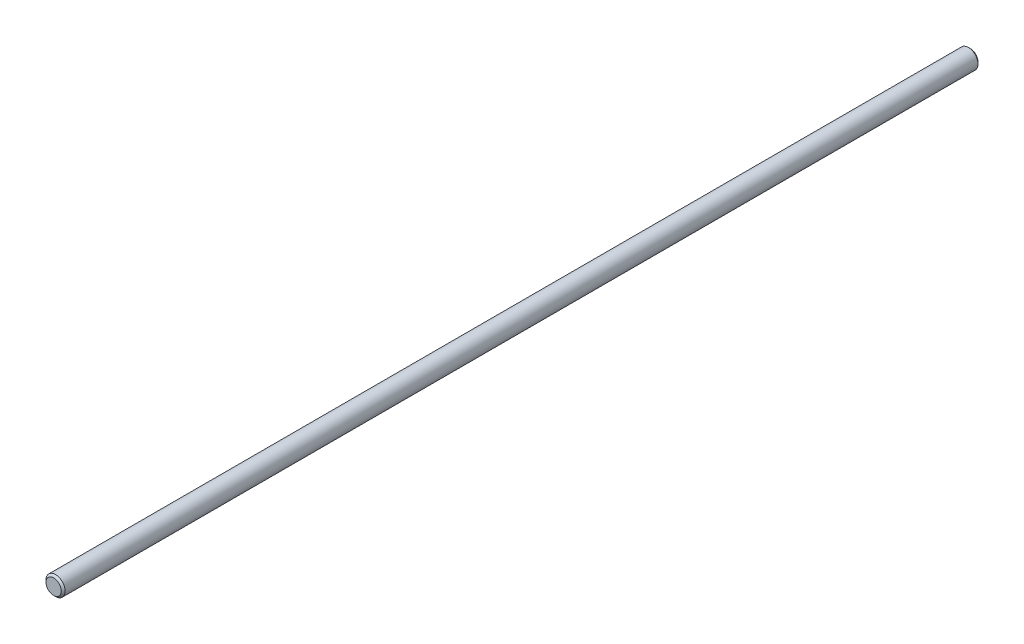
SolidWorks part; units mm, degrees
ref_plane "Front" through (0, 0, 0) normal (0, 0, 1) x (1, 0, 0)
ref_plane "Top" through (0, 0, 0) normal (0, 1, 0) x (1, 0, 0)
ref_plane "Right" through (0, 0, 0) normal (1, 0, 0) x (0, 0, -1)
sketch "Sketch1" plane through (0, 0, 0) normal (0, 0, 1) x (1, 0, 0)
  circle A0 centre (0, 0) radius 1.5875 construction
  dimension "Diameter" = 3.175
sketch "Sketch2" plane through (0, 0, 0) normal (1, 0, 0) x (0, 0, -1)
  line L0 (-76.2, 0) -> (76.2, 0) construction
  line L1 (5.2388, 0) -> (-5.2388, 0) construction
  line L3 (76.2, 1.5875) -> (76.2, -1.5875) construction
  line L4 (-76.2, 1.5875) -> (-76.2, -1.5875) construction
  line L5 (-72.2313, 1.5875) -> (-72.2313, -1.5875) construction
  line L6 (72.2313, 1.5875) -> (72.2313, -1.5875) construction
  point P6 (0, 0)
  point P10 (76.2, 0)
  point P13 (-76.2, 0)
  point P16 (-72.2313, 0)
  point P19 (72.2313, 0)
  dimension "D1" = 3.175
  dimension "Length" = 152.4
  dimension "D2" = 3.9688
  dimension "D3" = 3.9688
sketch "Sketch3" plane through (0, 0, 0) normal (0, 0, 1) x (1, 0, 0)
  line L0 (0, 1.5875) -> (0, -1.5875) construction
  circle A0 centre (0, 0) radius 1.5875
  dimension "D1" = 3.175
extrude "Boss-Extrude1" add sketch "Sketch3" along normal mid plane 152.4
chamfer "Chamfer1" distance 0.3175 angle 45 2 edges at (1.5875, 0, -76.2) (1.5875, 0, 76.2)
equation "\"D1@Sketch2\" = \"Diameter@Sketch1\""
equation "\"D1@Sketch3\" = \"Diameter@Sketch1\""
equation "\"D1@Boss-Extrude1\" = \"Length@Sketch2\""
equation "\"D1@Chamfer1\" = \"Diameter@Sketch1\" * .1"
equation "\"D2@Sketch2\"=\"Diameter@Sketch1\"*1.25"
equation "\"D3@Sketch2\"=\"D2@Sketch2\""
